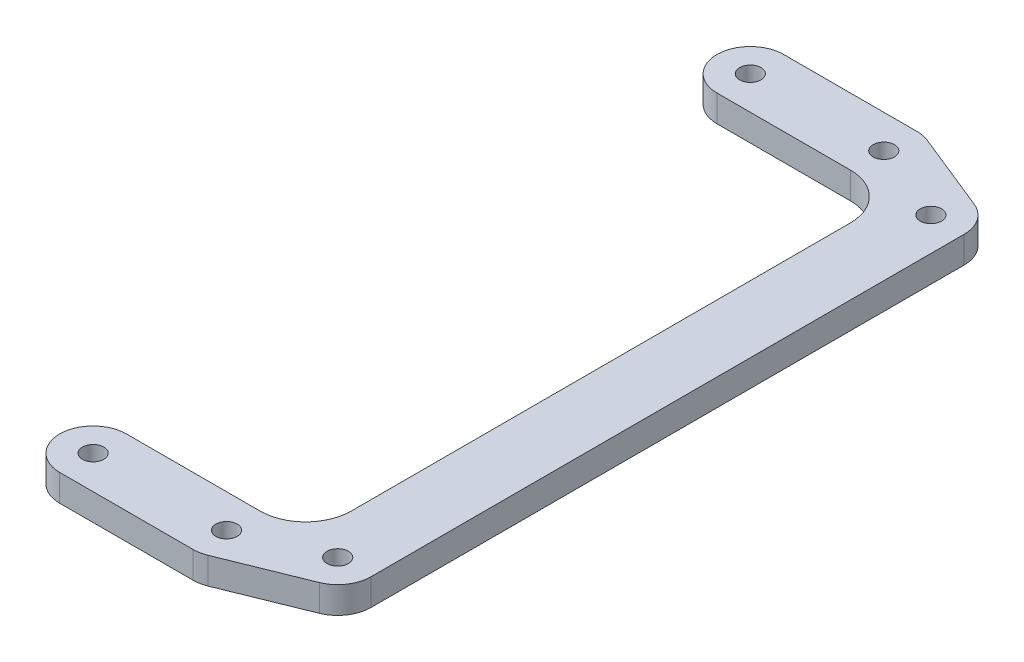
SolidWorks part; units mm, degrees
ref_plane "Спереди" through (0, 0, 0) normal (0, 0, 1) x (1, 0, 0)
ref_plane "Сверху" through (0, 0, 0) normal (0, 1, 0) x (1, 0, 0)
ref_plane "Справа" through (0, 0, 0) normal (1, 0, 0) x (0, 0, -1)
sketch "Sketch1" plane through (0, 0, 0) normal (0, 1, 0) x (1, 0, 0)
  line L0 (0, 0) -> (28.9283, 0) construction
  line L1 (-20, 49.25) -> (0, 49.25) construction
  line L2 (-20, 54.25) -> (0, 54.25)
  line L3 (0, 49.25) -> (0, -49.25) construction
  line L4 (11.86, 44.45) -> (11.86, -44.45) construction
  line L5 (-20, 44.25) -> (0, 44.25)
  line L6 (16.86, 44.45) -> (16.86, -44.45)
  line L7 (6.86, 44.45) -> (6.86, -44.45)
  line L8 (-20, -49.25) -> (0, -49.25) construction
  line L9 (-20, -54.25) -> (0, -54.25)
  line L10 (-20, -44.25) -> (0, -44.25)
  line L11 (1.8758, 53.8848) -> (13.7358, 49.0848)
  line L12 (1.8758, -53.8848) -> (13.7358, -49.0848)
  circle A0 centre (-20, 49.25) radius 1.6
  circle A1 centre (0, 49.25) radius 1.6
  circle A2 centre (0, -49.25) radius 1.6
  circle A3 centre (-20, -49.25) radius 1.6
  circle A4 centre (11.86, 44.45) radius 1.6
  circle A5 centre (11.86, -44.45) radius 1.6
  arc A6 (-20, 54.25) -> (-20, 44.25) centre (-20, 49.25) ccw
  arc A7 (0, 44.25) -> (0, 54.25) centre (0, 49.25) ccw
  arc A8 (16.86, 44.45) -> (6.86, 44.45) centre (11.86, 44.45) ccw
  arc A9 (6.86, -44.45) -> (16.86, -44.45) centre (11.86, -44.45) ccw
  arc A10 (-20, -54.25) -> (-20, -44.25) centre (-20, -49.25) cw
  arc A11 (0, -44.25) -> (0, -54.25) centre (0, -49.25) cw
  arc A12 (0, 44.25) -> (6.86, 37.39) centre (0, 37.39) cw
  arc A13 (0, -44.25) -> (6.86, -37.39) centre (0, -37.39) ccw
  point P14 (-10, 49.25)
  point P20 (11.86, 0)
  point P25 (-10, -49.25)
  point P40 (7.86, 37.39)
  dimension "D2" = 98.5
  dimension "D3" = 20
  dimension "D5" = 11.86
  dimension "D1" = 3.2
  dimension "D4" = 88.9
  dimension "D6" = 10
extrude "Boss-Extrude1" add sketch "Sketch1" along normal blind 4 contours L5 A7 L2 A6 A1 A0 | A7 A12 L7 A8 L11 | A9 L6 A8 L7 A5 A4 | A11 L10 A10 L9 A3 A2 | A13 A11 L12 A9 L7
